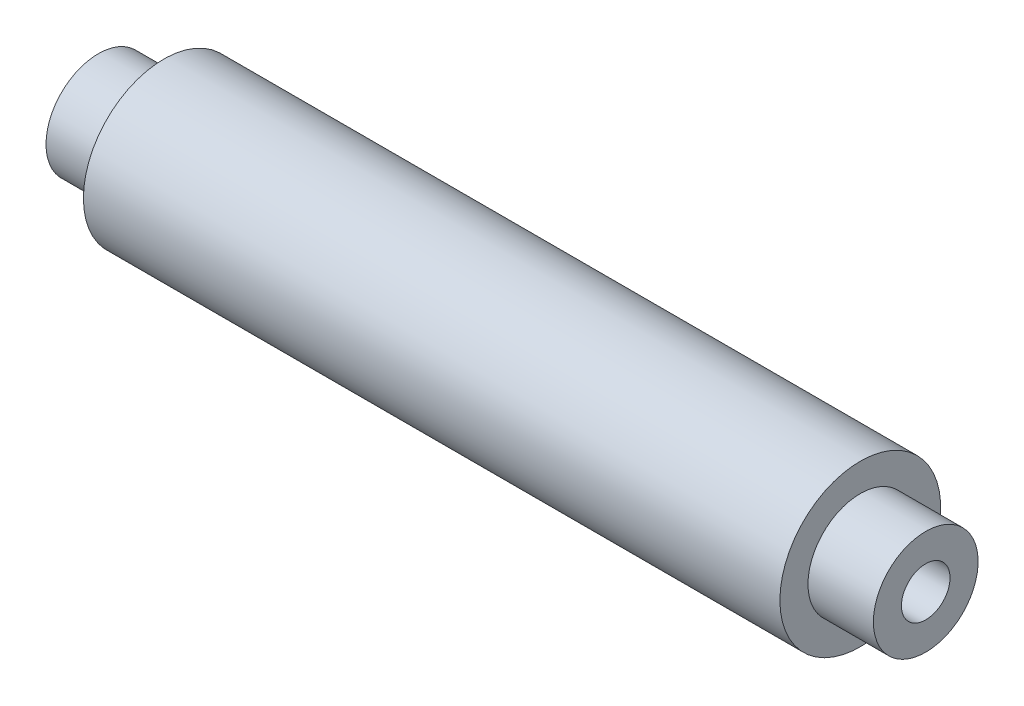
SolidWorks part; units mm, degrees
ref_plane "Front Plane" through (0, 0, 0) normal (0, 0, 1) x (1, 0, 0)
ref_plane "Top Plane" through (0, 0, 0) normal (0, 1, 0) x (1, 0, 0)
ref_plane "Right Plane" through (0, 0, 0) normal (1, 0, 0) x (0, 0, -1)
sketch "Sketch1" plane through (0, 0, 0) normal (0, 0, 1) x (1, 0, 0)
  line L0 (0, 0) -> (73.2003, 0) construction
  line L1 (0, 1.3) -> (12.5, 1.3)
  line L2 (44.25, 1.3) -> (44.25, 2.8)
  line L3 (44.25, 2.8) -> (40.75, 2.8)
  line L4 (40.75, 2.8) -> (40.75, 4.3)
  line L5 (40.75, 4.3) -> (3.5, 4.3)
  line L6 (3.5, 4.3) -> (3.5, 2.8)
  line L7 (3.5, 2.8) -> (0, 2.8)
  line L8 (0, 2.8) -> (0, 1.3)
  line L9 (31.75, 1.3) -> (31.75, 0)
  line L10 (31.75, 0) -> (12.5, 0)
  line L11 (12.5, 0) -> (12.5, 1.3)
  line L12 (31.75, 1.3) -> (44.25, 1.3)
  point P10 (3.5, 3.55)
  dimension "D1" = 37.25
  dimension "D2" = 1.5
  dimension "D3" = 3.5
  dimension "D4" = 12.5
  dimension "D5" = 1.5
  dimension "D6" = 1.3
revolve "Revolve1" add sketch "Sketch1" angle 360 about L0
